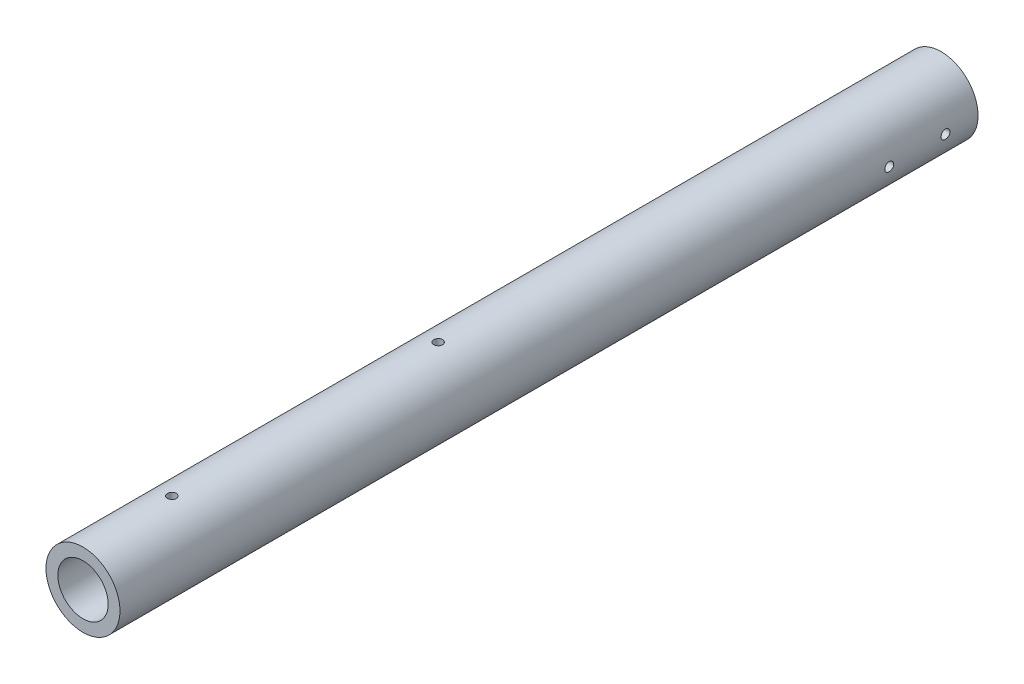
SolidWorks part; units mm, degrees
ref_plane "Front Plane" through (0, 0, 0) normal (0, 0, 1) x (1, 0, 0)
ref_plane "Top Plane" through (0, 0, 0) normal (0, 1, 0) x (1, 0, 0)
ref_plane "Right Plane" through (0, 0, 0) normal (1, 0, 0) x (0, 0, -1)
sketch "Sketch1" plane through (0, 0, 0) normal (0, 0, 1) x (1, 0, 0)
  circle A0 centre (0, 0) radius 8.5
  circle A1 centre (0, 0) radius 12.5
  dimension "D1" = 17
  dimension "D2" = 4
extrude "Boss-Extrude1" add sketch "Sketch1" along normal blind 400
sketch "Sketch2" plane through (0, 0, 0) normal (0, 1, 0) x (1, 0, 0)
  line L0 (-12.5, -400) -> (12.5, -400) construction
  circle A0 centre (0, -370) radius 1.5
  circle A1 centre (0, -280) radius 1.5
  dimension "D3" = 3
  dimension "D4" = 3
  dimension "D1" = 90
  dimension "D2" = 30
extrude "Cut-Extrude1" cut sketch "Sketch2" against normal through all both and the other way through all
sketch "Sketch3" plane through (0, 0, 0) normal (1, 0, 0) x (0, 0, -1)
  line L0 (-400, 12.5) -> (-400, -12.5) construction
  circle A0 centre (-121, 0) radius 1.5
  circle A1 centre (-140, 0) radius 1.5
  dimension "D3" = 3
  dimension "D4" = 3
  dimension "D1" = 260
  dimension "D2" = 19
extrude "Cut-Extrude2" cut sketch "Sketch3" against normal through all both and the other way through all
sketch "Sketch4" plane through (0, 0, 0) normal (0, 0, -1) x (-1, 0, 0)
  circle A0 centre (0, 0) radius 16.4095
extrude "Cut-Extrude3" cut sketch "Sketch4" against normal blind 110 and the other way through all
